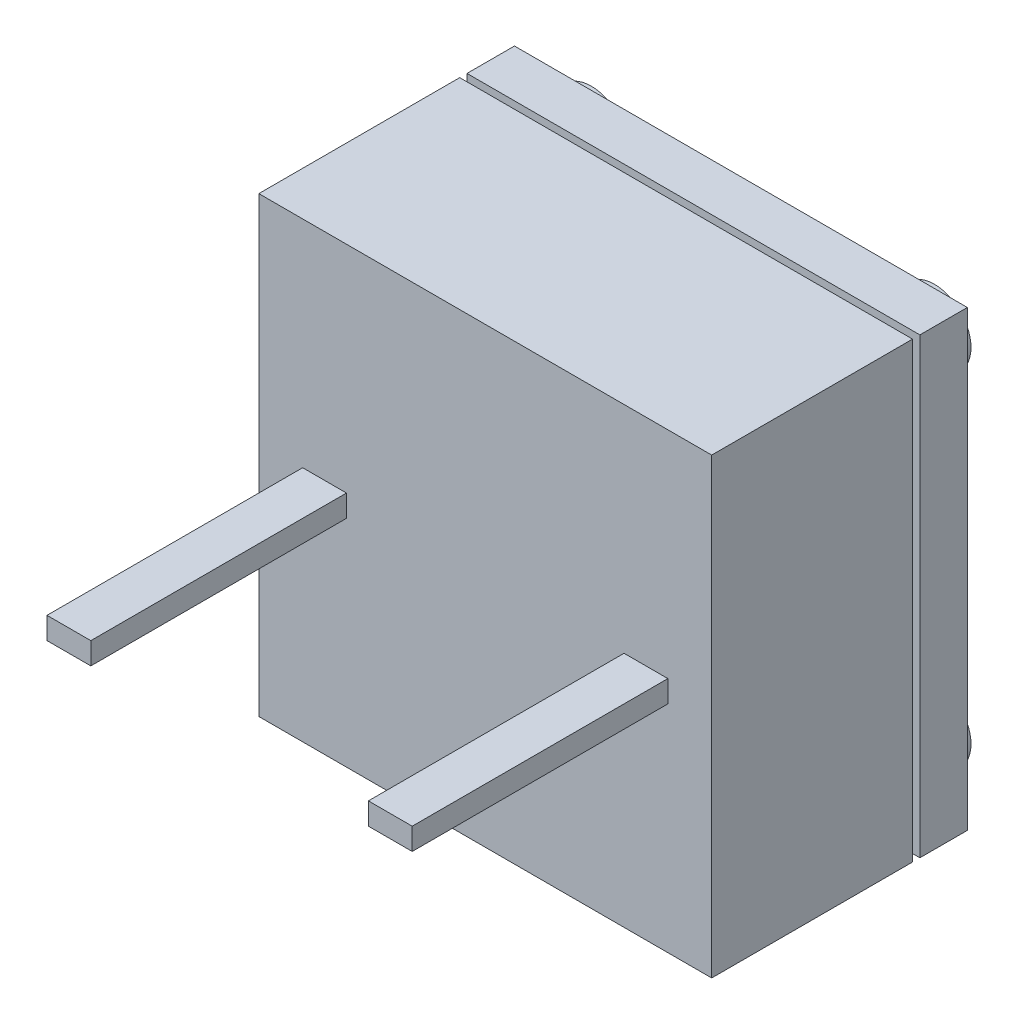
SolidWorks part; units mm, degrees
ref_plane "Front" through (0, 0, 0) normal (0, 0, 1) x (1, 0, 0)
ref_plane "Top" through (0, 0, 0) normal (0, 1, 0) x (1, 0, 0)
ref_plane "Right" through (0, 0, 0) normal (1, 0, 0) x (0, 0, -1)
sketch "Croquis1" plane through (0, 0, 0) normal (0, 0, 1) x (1, 0, 0)
  line L0 (0, 0) -> (0, 6.2)
  line L1 (0, 6.2) -> (6.2, 6.2)
  line L2 (0, 0) -> (6.2, 0)
  line L3 (6.2, 0) -> (6.2, 6.2)
extrude "Saliente-Extruir1" add sketch "Croquis1" along normal blind 3.5
sketch "Croquis2" plane through (0, 6.2, 0) normal (0, 1, 0) x (1, 0, 0)
  line L0 (0, -0.65) -> (6.2, -0.65)
  line L2 (0, -0.65) -> (0, -0.75)
  line L3 (0, -3.5) -> (0, 0) construction
  line L4 (0, -0.75) -> (6.2, -0.75)
  line L5 (6.2, -3.5) -> (6.2, 0) construction
  line L6 (6.2, -0.65) -> (6.2, -0.75)
  dimension "D1" = 0.1
extrude "Cortar-Extruir1" cut sketch "Croquis2" against normal blind 0.1
sketch "Croquis3" plane through (0, 6.1, 0) normal (0, 1, 0) x (1, 0, 0)
  line L0 (0, -0.65) -> (0, -0.75)
  line L1 (0, -0.75) -> (0.1, -0.75)
  line L2 (0, -0.75) -> (6.2, -0.75) construction
  line L3 (0, -0.65) -> (0.1, -0.65)
  line L4 (6.2, -0.65) -> (0, -0.65) construction
  line L5 (0.1, -0.65) -> (0.1, -0.75)
  line L6 (6.2, -0.65) -> (6.1, -0.65)
  line L7 (6.1, -0.65) -> (6.1, -0.75)
  line L8 (0, -0.75) -> (6.2, -0.75) construction
  line L9 (6.1, -0.75) -> (6.2, -0.75)
  line L10 (6.2, -0.75) -> (6.2, -0.65)
extrude "Cortar-Extruir2" cut sketch "Croquis3" against normal through all both and the other way through all contours L10 L6 L7 L9 | L5 L1 L0 L3
sketch "Croquis4" plane through (0.1, 0, 0) normal (-1, 0, 0) x (0, 0, 1)
  line L0 (0.65, 0) -> (0.65, 0.1)
  line L1 (0.65, 0) -> (0.65, 6.1) construction
  line L2 (0.65, 0.1) -> (0.75, 0.1)
  line L3 (0.75, 0) -> (0.75, 6.1) construction
  line L4 (0.75, 0.1) -> (0.75, 0)
  line L5 (0.75, 0) -> (0.65, 0)
extrude "Cortar-Extruir3" cut sketch "Croquis4" against normal through all both and the other way through all
sketch "Croquis5" plane through (0, 0, 0) normal (0, 0, -1) x (-1, 0, 0)
  circle A0 centre (-3.1, 3.1) radius 1.75
extrude "Saliente-Extruir2" add sketch "Croquis5" along normal blind 1 contours A0
sketch "Croquis6" plane through (0, 0, 0) normal (0, 0, -1) x (-1, 0, 0)
  circle A0 centre (-0.75, 0.75) radius 0.5
  circle A1 centre (-5.45, 0.75) radius 0.5
  circle A2 centre (-0.75, 5.45) radius 0.5
  circle A3 centre (-5.45, 5.45) radius 0.5
extrude "Saliente-Extruir3" add sketch "Croquis6" along normal blind 0.3
sketch "Croquis8" plane through (0, 0, 3.5) normal (0, 0, 1) x (1, 0, 0)
  line L7 (5.6, 2.95) -> (5.6, 3.1)
  line L8 (0.6, 2.95) -> (0.6, 3.1)
  line L9 (5.6, 3.1) -> (5.6, 3.25)
  line L10 (0.6, 3.1) -> (0.6, 3.25)
  line L11 (0.6, 3.25) -> (1.2, 3.25)
  line L12 (5.6, 3.25) -> (5, 3.25)
  line L13 (0.6, 2.95) -> (1.2, 2.95)
  line L14 (5, 3.25) -> (5, 2.95)
  line L15 (1.2, 3.25) -> (1.2, 2.95)
  line L17 (5, 2.95) -> (5.6, 2.95)
extrude "Saliente-Extruir4" add sketch "Croquis8" along normal blind 3.5
